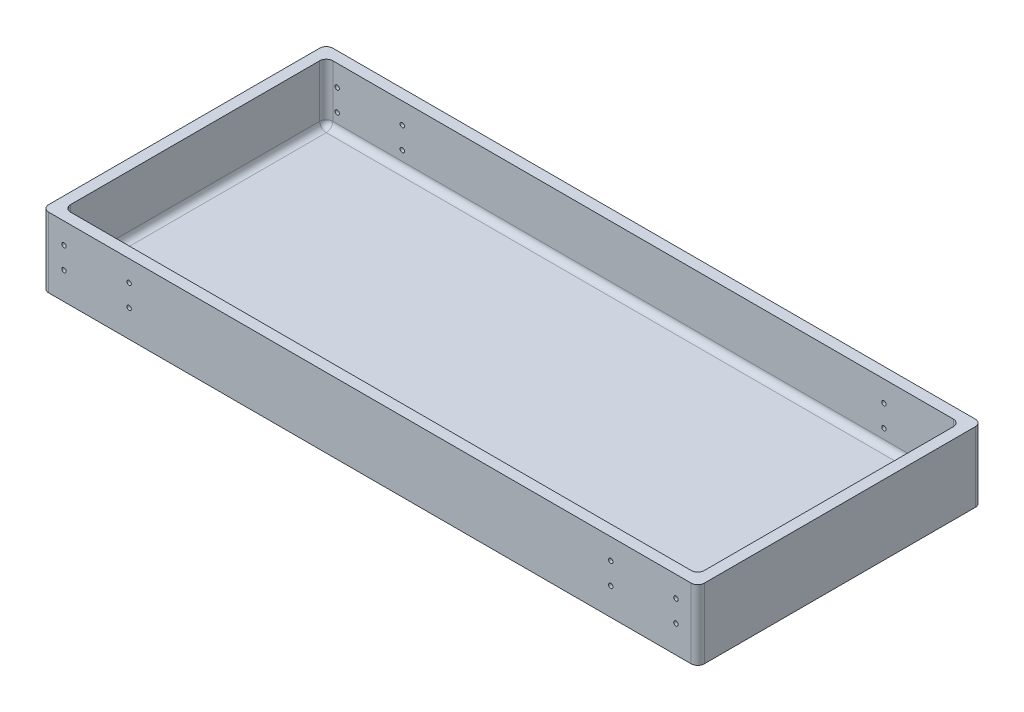
SolidWorks part; units mm, degrees
ref_plane "Front Plane" through (0, 0, 0) normal (0, 0, 1) x (1, 0, 0)
ref_plane "Top Plane" through (0, 0, 0) normal (0, 1, 0) x (1, 0, 0)
ref_plane "Right Plane" through (0, 0, 0) normal (1, 0, 0) x (0, 0, -1)
sketch "Sketch1" plane through (0, 0, 0) normal (0, 1, 0) x (1, 0, 0)
  line L1 (-150, -65) -> (150, -65)
  line L2 (-150, -65) -> (-150, 65)
  line L3 (-150, 65) -> (150, 65)
  line L4 (150, -65) -> (150, 65)
  line L5 (-150, -65) -> (150, 65) construction
  line L6 (-150, 65) -> (150, -65) construction
  point P0 (0, 0)
  dimension "D1" = 130
  dimension "D2" = 300
extrude "Boss-Extrude1" add sketch "Sketch1" along normal blind 32
shell "Shell1" thickness 5
sketch3d "3DSketch1"
  point P0 (-114.2859, 14.8906, 65)
sketch "Sketch3" plane through (0, 0, 65) normal (0, 0, 1) x (1, 0, 0)
  line L0 (-150, 32) -> (-150, 0) construction
  line L2 (-150, 32) -> (150, 32) construction
  circle A0 centre (-140, 22.4) radius 1
  circle A1 centre (-110.2, 22.4) radius 1
  circle A2 centre (-140, 12.5) radius 1
  circle A3 centre (-110.2, 12.5) radius 1
  dimension "D3" = 2
  dimension "D4" = 2
  dimension "D5" = 2
  dimension "D8" = 2
  dimension "D1" = 29.8
  dimension "D2" = 10
  dimension "D6" = 9.9
  dimension "D7" = 9.6
extrude "Cut-Extrude1" cut sketch "Sketch3" against normal through all
mirror "Mirror1" about plane through (0, 0, 0) normal (1, 0, 0) of "Cut-Extrude1"
fillet "Fillet1" radius 3 1 edges at (145, 5, 0)
fillet "Fillet2" radius 3 3 edges at (145, 20, -60) (-1.5, 5, -60) (144.1213, 5.8787, -60)
fillet "Fillet3" radius 3 3 edges at (-145, 20, -60) (-145, 5, 1.5) (-145, 5.8787, -59.1213)
fillet "Fillet4" radius 3 5 edges at (0, 5, 60) (-144.1213, 5.8787, 60) (145, 20, 60) (-145, 20, 60) (144.1213, 5.8787, 60)
fillet "Fillet5" radius 3 1 edges at (150, 16, -65)
fillet "Fillet6" radius 3 1 edges at (-150, 16, -65)
fillet "Fillet7" radius 3 1 edges at (-150, 16, 65)
fillet "Fillet8" radius 3 1 edges at (150, 16, 65)
